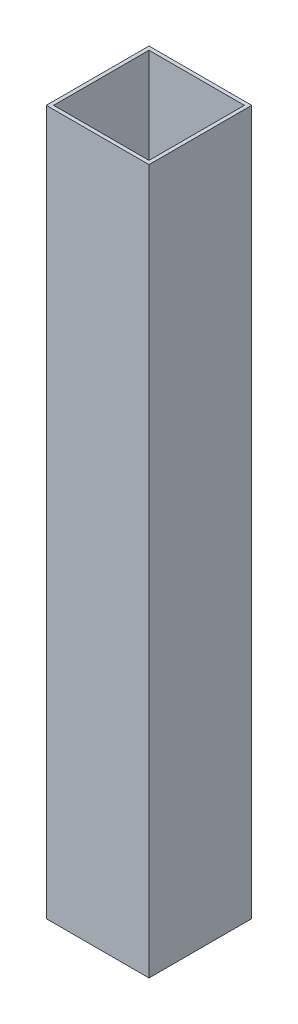
SolidWorks part; units mm, degrees
ref_plane "Front Plane" through (0, 0, 0) normal (0, 0, 1) x (1, 0, 0)
ref_plane "Top Plane" through (0, 0, 0) normal (0, 1, 0) x (1, 0, 0)
ref_plane "Right Plane" through (0, 0, 0) normal (1, 0, 0) x (0, 0, -1)
other "Configuration Table"
sketch "Sketch1" plane through (0, 0, 0) normal (0, 1, 0) x (1, 0, 0)
  line L1 (22.225, 22.225) -> (-22.225, 22.225)
  line L2 (22.225, 22.225) -> (22.225, -22.225)
  line L3 (22.225, -22.225) -> (-22.225, -22.225)
  line L4 (-22.225, 22.225) -> (-22.225, -22.225)
  line L5 (22.225, 22.225) -> (-22.225, -22.225) construction
  line L6 (22.225, -22.225) -> (-22.225, 22.225) construction
  line L7 (20.6375, -20.6375) -> (-20.6375, -20.6375)
  line L8 (20.6375, -20.6375) -> (20.6375, 20.6375)
  line L9 (20.6375, 20.6375) -> (-20.6375, 20.6375)
  line L10 (-20.6375, -20.6375) -> (-20.6375, 20.6375)
  line L11 (20.6375, -20.6375) -> (-20.6375, 20.6375) construction
  line L12 (20.6375, 20.6375) -> (-20.6375, -20.6375) construction
  point P0 (0, 0)
  point P6 (0, 0)
  dimension "D1" = 44.45
  dimension "D2" = 1.5875
extrude "Boss-Extrude1" add sketch "Sketch1" along normal blind 304.8
